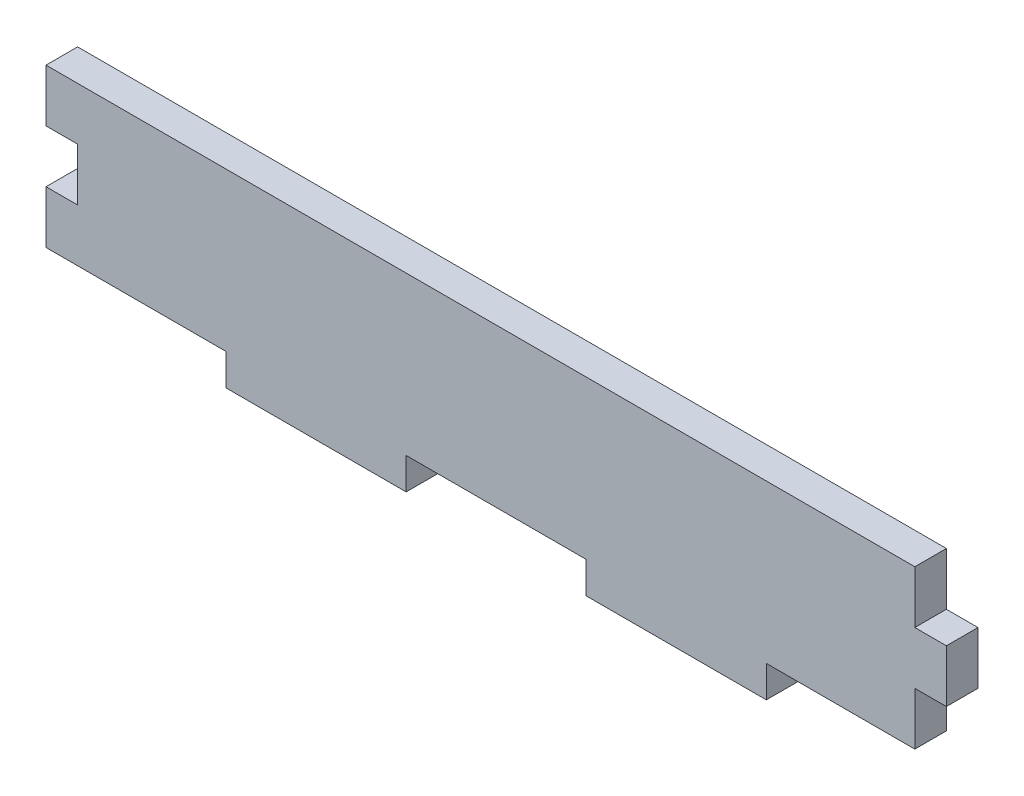
SolidWorks part; units mm, degrees
ref_plane "Front Plane" through (0, 0, 0) normal (0, 0, 1) x (1, 0, 0)
ref_plane "Top Plane" through (0, 0, 0) normal (0, 1, 0) x (1, 0, 0)
ref_plane "Right Plane" through (0, 0, 0) normal (1, 0, 0) x (0, 0, -1)
sketch "Sketch1" plane through (0, 0, 0) normal (0, 0, 1) x (1, 0, 0)
  line L1 (0, 0) -> (144.78, 0)
  line L2 (0, 0) -> (0, 30.48)
  line L3 (0, 30.48) -> (144.78, 30.48)
  line L4 (144.78, 0) -> (144.78, 30.48)
  dimension "D1" = 144.78
  dimension "D2" = 30.48
extrude "Boss-Extrude1" add sketch "Sketch1" along normal blind 5.08
sketch "Sketch2" plane through (0, 0, 5.08) normal (0, 0, 1) x (1, 0, 0)
  line L0 (0, 30.48) -> (0, 0) construction
  line L1 (0, 5.08) -> (28.956, 5.08)
  line L2 (0, 5.08) -> (0, 0)
  line L3 (0, 0) -> (28.956, 0)
  line L4 (28.956, 5.08) -> (28.956, 0)
  line L5 (0, 0) -> (144.78, 0) construction
  line L6 (28.956, 5.08) -> (57.912, 5.08) construction
  line L7 (57.912, 0) -> (86.868, 0)
  line L8 (57.912, 0) -> (57.912, 5.08)
  line L9 (57.912, 5.08) -> (86.868, 5.08)
  line L10 (86.868, 0) -> (86.868, 5.08)
  line L11 (144.78, 0) -> (115.824, 0)
  line L12 (144.78, 0) -> (144.78, 5.08)
  line L13 (144.78, 5.08) -> (115.824, 5.08)
  line L14 (115.824, 0) -> (115.824, 5.08)
  line L15 (86.868, 5.08) -> (115.824, 5.08) construction
  dimension "D1" = 5.08
extrude "Cut-Extrude1" cut sketch "Sketch2" against normal through all
sketch "Sketch3" plane through (0, 0, 5.08) normal (0, 0, 1) x (1, 0, 0)
  line L0 (0, 30.48) -> (0, 5.08) construction
  line L1 (0, 22.0133) -> (5.08, 22.0133)
  line L2 (0, 22.0133) -> (0, 13.5467)
  line L3 (0, 13.5467) -> (5.08, 13.5467)
  line L4 (5.08, 22.0133) -> (5.08, 13.5467)
  line L5 (5.08, 22.0133) -> (5.08, 30.48) construction
  line L6 (144.78, 30.48) -> (0, 30.48) construction
  line L7 (5.08, 13.5467) -> (5.08, 5.08) construction
  line L8 (28.956, 5.08) -> (0, 5.08) construction
  line L9 (139.7, 22.0133) -> (139.7, 13.5467) construction
  line L10 (144.78, 30.48) -> (139.7, 30.48)
  line L11 (144.78, 30.48) -> (144.78, 22.0133)
  line L12 (144.78, 22.0133) -> (139.7, 22.0133)
  line L13 (139.7, 30.48) -> (139.7, 22.0133)
  line L14 (144.78, 5.08) -> (139.7, 5.08)
  line L15 (144.78, 5.08) -> (144.78, 13.5467)
  line L16 (144.78, 13.5467) -> (139.7, 13.5467)
  line L17 (139.7, 5.08) -> (139.7, 13.5467)
  dimension "D1" = 5.08
  dimension "D2" = 5.08
extrude "Cut-Extrude2" cut sketch "Sketch3" against normal through all
equation "\"MDF\"= .2"
equation "\"Foamcore\"= .1"
equation "\"GMaterial\"= \"MDF\""
equation "\"CutDistance\" = .1"
equation "\"D1@Sketch1\"=\"GMaterial\"+5.5"
equation "\"D2@Sketch1\"=\"GMaterial\" + 1"
equation "\"D1@Boss-Extrude1\"=\"GMaterial\""
equation "\"D1@Sketch2\"=\"GMaterial\""
equation "\"D1@Sketch3\"=\"GMaterial\""
equation "\"D2@Sketch3\"=\"GMaterial\""
